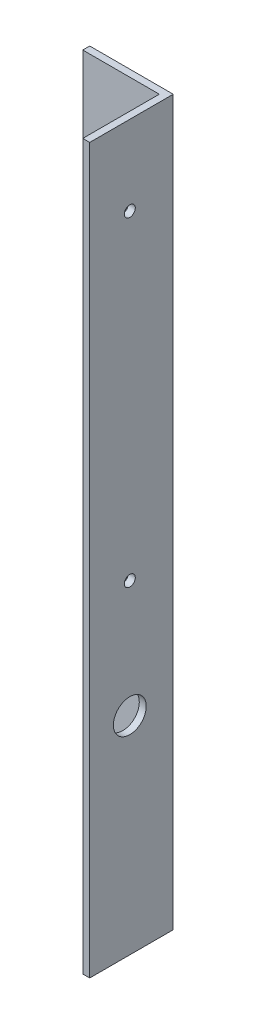
SolidWorks part; units mm, degrees
ref_plane "Front Plane" through (0, 0, 0) normal (0, 0, 1) x (1, 0, 0)
ref_plane "Top Plane" through (0, 0, 0) normal (0, 1, 0) x (1, 0, 0)
ref_plane "Right Plane" through (0, 0, 0) normal (1, 0, 0) x (0, 0, -1)
sketch "Sketch1" plane through (0, 0, 0) normal (0, 1, 0) x (1, 0, 0)
  line L0 (15.875, -19.05) -> (15.875, 15.875)
  line L1 (-19.05, 19.05) -> (19.05, 19.05)
  line L2 (-19.05, 19.05) -> (-19.05, -19.05) construction
  line L3 (-19.05, -19.05) -> (19.05, -19.05) construction
  line L4 (19.05, 19.05) -> (19.05, -19.05)
  line L5 (-19.05, 19.05) -> (19.05, -19.05) construction
  line L6 (-19.05, -19.05) -> (19.05, 19.05) construction
  line L7 (15.875, 15.875) -> (-19.05, 15.875)
  line L8 (-19.05, 15.875) -> (-19.05, 19.05)
  line L9 (15.875, -19.05) -> (19.05, -19.05)
  point P0 (0, 0)
  dimension "D1" = 38.1
  dimension "D2" = 3.175
extrude "Boss-Extrude1" add sketch "Sketch1" along normal mid plane 330.2
sketch "Sketch2" plane through (19.05, 0, 0) normal (1, 0, 0) x (0, 0, -1)
  line L0 (-32.722, 201.3839) -> (-0.762, 201.3839) construction
  line L1 (-32.722, 201.3839) -> (-32.722, 128.8161) construction
  line L2 (-32.722, 128.8161) -> (-32.722, -17.2339) construction
  line L3 (-32.722, -17.2339) -> (-32.722, -70.5739) construction
  line L4 (-32.722, -70.5739) -> (-0.762, -70.5739) construction
  line L5 (-0.762, 201.3839) -> (-0.762, -70.5739) construction
  line L6 (-32.722, 128.8161) -> (-0.762, 128.8161) construction
  line L7 (-32.722, -17.2339) -> (-0.762, -17.2339) construction
  line L8 (-16.742, 201.3839) -> (-16.742, 128.8161) construction
  line L9 (19.05, 165.1) -> (19.05, -165.1) construction
  line L11 (-19.05, 165.1) -> (19.05, 165.1) construction
  circle A0 centre (-32.722, 128.8161) radius 2.5
  circle A1 centre (-32.722, 201.3839) radius 7.5
  circle A2 centre (-32.722, -17.2339) radius 2.5
  circle A3 centre (-32.722, -70.5739) radius 7.5
  circle A4 centre (-0.762, -70.5739) radius 7.5
  circle A5 centre (-0.762, 201.3839) radius 7.5
  circle A6 centre (-0.762, 128.8161) radius 2.5
  circle A7 centre (-0.762, -17.2339) radius 2.5
  point P18 (-16.742, 165.1)
  dimension "D3" = 15
  dimension "D4" = 5
  dimension "D1" = 146.05
  dimension "D2" = 31.96
  dimension "D5" = 53.34
  dimension "D6" = 72.5678
  dimension "D7" = 19.812
extrude "Cut-Extrude1" cut sketch "Sketch2" against normal through all both and the other way through all
